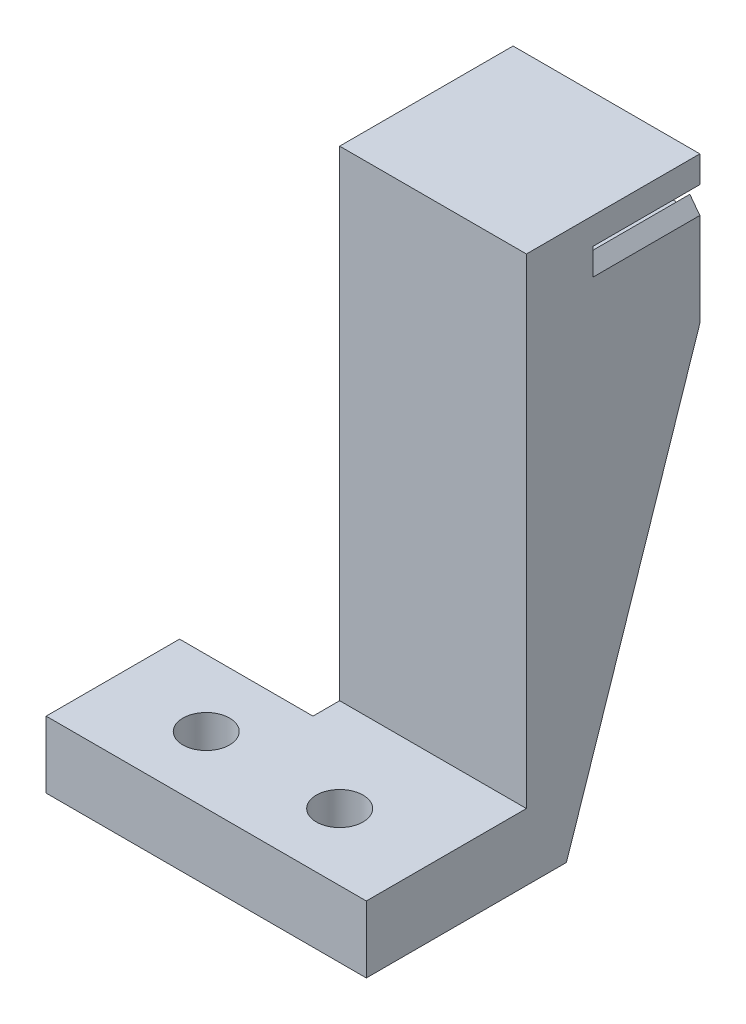
SolidWorks part; units mm, degrees
ref_plane "前视基准面" through (0, 0, 0) normal (0, 0, 1) x (1, 0, 0)
ref_plane "上视基准面" through (0, 0, 0) normal (0, 1, 0) x (1, 0, 0)
ref_plane "右视基准面" through (0, 0, 0) normal (1, 0, 0) x (0, 0, -1)
sketch "草图1" plane through (0, 0, 0) normal (0, 0, 1) x (1, 0, 0)
  line L1 (-22, -13.5) -> (22, -13.5)
  line L2 (-22, -13.5) -> (-22, 13.5)
  line L3 (-22, 13.5) -> (22, 13.5)
  line L4 (22, -13.5) -> (22, 13.5)
  line L5 (-22, -13.5) -> (22, 13.5) construction
  line L6 (-22, 13.5) -> (22, -13.5) construction
  circle A0 centre (-10, 9.5) radius 1.75
  circle A1 centre (-10, -4.5) radius 1.75
  circle A2 centre (10, 9.5) radius 1.75
  circle A3 centre (10, -4.5) radius 1.75
  point P0 (0, 0)
  dimension "D3" = 3.5
  dimension "D4" = 4
  dimension "D5" = 3.5
  dimension "D6" = 14
  dimension "D7" = 20
  dimension "D8" = 4
  dimension "D9" = 3.5
  dimension "D10" = 12
  dimension "D11" = 12
  dimension "D12" = 3.5
  dimension "D13" = 20
  dimension "D14" = 14
  dimension "D1" = 44
  dimension "D2" = 27
extrude "凸台-拉伸1" add sketch "草图1" along normal blind 8
sketch "草图3" plane through (0, 0, 8) normal (0, 0, 1) x (1, 0, 0)
  line L0 (-22, 6) -> (22, 6)
  line L1 (-22, 13.5) -> (-22, -13.5) construction
  line L2 (22, -13.5) -> (22, 13.5) construction
  line L3 (22, 6) -> (22, 13.5)
  line L4 (22, 13.5) -> (-22, 13.5)
  line L5 (-22, 13.5) -> (-22, 6)
  line L6 (-22, 3.5) -> (-17, 3.5)
  line L7 (-17, 3.5) -> (-10, -3.5)
  line L8 (-10, -3.5) -> (-22, -3.5)
  line L9 (-22, -3.5) -> (-22, 3.5)
  line L10 (-13.4645, 3.5) -> (-7.3431, -2.6213)
  line L11 (0, 0) -> (0, -13.5) construction
  line L12 (-22, -13.5) -> (22, -13.5) construction
  line L13 (22, 3.5) -> (17, 3.5)
  line L14 (22, -3.5) -> (22, 3.5)
  line L15 (10, -3.5) -> (22, -3.5)
  line L16 (17, 3.5) -> (10, -3.5)
  line L17 (13.4645, 3.5) -> (7.3431, -2.6213)
  arc A0 (-7.3431, -2.6213) -> (-3.1005, 1.6213) centre (-5.2218, -0.5) ccw
  arc A1 (-13.4645, 3.5) -> (-3.1005, 1.6213) centre (-9.6378, -4.9159) cw
  circle A2 centre (-10, 9.5) radius 3
  arc A3 (7.3431, -2.6213) -> (3.1005, 1.6213) centre (5.2218, -0.5) cw
  arc A4 (13.4645, 3.5) -> (3.1005, 1.6213) centre (9.6378, -4.9159) ccw
  circle A5 centre (10, 9.5) radius 3
  dimension "D7" = 3
  dimension "D8" = 6
  dimension "D1" = 7.5
  dimension "D2" = 7
  dimension "D3" = 2.5
  dimension "D4" = 45
  dimension "D5" = 12
  dimension "D6" = 2.5
  dimension "D9" = 6
extrude "凸台-拉伸2" add sketch "草图3" along normal blind 6.5
sketch "草图4" plane through (0, 0, 8) normal (0, 0, 1) x (1, 0, 0)
  circle A0 centre (-10, -4.5) radius 2.5
  circle A1 centre (10, 9.5) radius 3
  circle A2 centre (10, 9.5) radius 3
  circle A3 centre (-10, 9.5) radius 3
  circle A4 centre (-10, 9.5) radius 3
  circle A5 centre (10, -4.5) radius 2.5
  dimension "D3" = 5
  dimension "D4" = 5
  dimension "D1" = 0
  dimension "D2" = 0
extrude "切除-拉伸1" cut sketch "草图4" against normal blind 2.5
sketch "草图5" plane through (0, 0, 0) normal (0, 0, 1) x (1, 0, 0)
  line L0 (-22, -13.5) -> (22, -13.5)
  line L1 (22, -13.5) -> (22, -31.5)
  line L2 (22, -31.5) -> (-22, -31.5)
  line L3 (-22, -31.5) -> (-22, -13.5)
  dimension "D1" = 18
extrude "凸台-拉伸3" add sketch "草图5" along normal blind 18
sketch "草图6" plane through (0, 0, 18) normal (0, 0, 1) x (1, 0, 0)
  line L0 (-22, -15.5) -> (22, -15.5)
  line L1 (-22, -13.5) -> (-22, -31.5) construction
  line L2 (22, -31.5) -> (22, -13.5) construction
  line L3 (22, -15.5) -> (22, -19.5)
  line L4 (22, -19.5) -> (-22, -19.5)
  line L5 (-22, -19.5) -> (-22, -15.5)
  line L6 (-22, -13.5) -> (22, -13.5) construction
  line L7 (-22, -25.5) -> (22, -25.5)
  line L8 (22, -25.5) -> (22, -29)
  line L9 (22, -29) -> (-22, -29)
  line L10 (-22, -29) -> (-22, -25.5)
  dimension "D1" = 4
  dimension "D2" = 2
  dimension "D3" = 6
  dimension "D4" = 3.5
extrude "切除-拉伸2" cut sketch "草图6" against normal blind 2.5 contours L0 L3 L4 L5
sketch "草图7" plane through (0, 0, 18) normal (0, 0, 1) x (1, 0, 0)
  line L2 (-22, -19.5) -> (22, -19.5) construction
  line L3 (-22, -19.5) -> (22, -19.5) construction
  line L4 (-22, -19.5) -> (-22, -25.5) construction
  circle A0 centre (-12, -22.5) radius 1.75
  circle A1 centre (12, -22.5) radius 1.75
  dimension "D1" = 3.5
  dimension "D2" = 3.5
  dimension "D3" = 24
  dimension "D4" = 10
  dimension "D5" = 3
  dimension "D6" = 3
extrude "切除-拉伸3" cut sketch "草图7" against normal through all
sketch "草图8" plane through (0, 0, 0) normal (0, 0, -1) x (-1, 0, 0)
  line L0 (0, 0) -> (0, -31.5) construction
  line L1 (-15, -25.5) -> (-9, -25.5)
  line L2 (-15, -25.5) -> (-15, -19.5)
  line L3 (-15, -19.5) -> (-9, -19.5)
  line L4 (-9, -25.5) -> (-9, -19.5)
  line L5 (-15, -25.5) -> (-9, -19.5) construction
  line L6 (-15, -19.5) -> (-9, -25.5) construction
  line L7 (22, -31.5) -> (-22, -31.5) construction
  line L8 (15, -19.5) -> (9, -25.5) construction
  line L9 (15, -25.5) -> (9, -19.5) construction
  line L10 (9, -25.5) -> (9, -19.5)
  line L11 (15, -19.5) -> (9, -19.5)
  line L12 (15, -25.5) -> (15, -19.5)
  line L13 (15, -25.5) -> (9, -25.5)
  point P0 (-12, -22.5)
  point P15 (12, -22.5)
  dimension "D1" = 6
  dimension "D2" = 6
extrude "切除-拉伸4" cut sketch "草图8" against normal blind 4
sketch "草图9" plane through (0, 0, 18) normal (0, 0, 1) x (1, 0, 0)
  line L0 (-22, -13.5) -> (22, -13.5)
  line L1 (22, -13.5) -> (22, -31.5)
  line L2 (22, -31.5) -> (-22, -31.5)
  line L3 (-22, -31.5) -> (-22, -13.5)
extrude "切除-拉伸5" cut sketch "草图9" against normal through all
sketch "草图10" plane through (0, -13.5, 0) normal (0, -1, 0) x (1, 0, 0)
  line L0 (-22, 8) -> (22, 8)
  line L1 (22, 8) -> (22, 14.5)
  line L2 (22, 14.5) -> (-22, 14.5)
  line L3 (-22, 14.5) -> (-22, 8)
  line L4 (-22, 8) -> (-21.8348, 7.9647)
  line M4 (22, 8) -> (-22, 8)
extrude "切除-拉伸6" cut sketch "草图10" against normal through all contours L2 L3 L1 M4
sketch "草图11" plane through (0, -13.5, 0) normal (0, -1, 0) x (1, 0, 0)
  line L4 (-22, 8) -> (-22, 0)
  line L5 (-22, 0) -> (22, 0)
  line L6 (22, 0) -> (22, 8)
  line L7 (22, 8) -> (-22, 8)
  line L8 (-22, 8) -> (-22, 0)
  line L9 (-22, 0) -> (22, 0)
  line L10 (22, 0) -> (22, 8)
  line L11 (22, 8) -> (-22, 8)
  dimension "D1" = 0
extrude "凸台-拉伸4" add sketch "草图11" along normal blind 35
sketch "草图12" plane through (0, 0, 8) normal (0, 0, 1) x (1, 0, 0)
  circle A0 centre (-10, -4.5) radius 3
  circle A1 centre (10, -4.5) radius 3
  circle A3 centre (-10, 9.5) radius 3 construction
  dimension "D1" = 6
  dimension "D2" = 6
  dimension "D3" = 14
  dimension "D4" = 20
extrude "切除-拉伸7" cut sketch "草图12" against normal up to surface (2.5 mm away) up to face at (-8.25, -4.5, 5.5)
sketch "草图13" plane through (0, 0, 0) normal (0, 0, -1) x (-1, 0, 0)
  line L0 (-22, -40.5) -> (22, -40.5)
  line L1 (-22, -48.5) -> (-22, 13.5) construction
  line L2 (22, 13.5) -> (22, -48.5) construction
  line L3 (22, -40.5) -> (22, -43.5)
  line L4 (22, -43.5) -> (-22, -43.5)
  line L5 (-22, -43.5) -> (-22, -40.5)
  line L6 (22, -48.5) -> (-22, -48.5) construction
  dimension "D1" = 3
  dimension "D2" = 5
extrude "凸台-拉伸5" add sketch "草图13" along normal blind 10
sketch "草图14" plane through (0, 0, 0) normal (0, 0, -1) x (-1, 0, 0)
  line L0 (-22, -48.5) -> (22, -48.5)
  line L1 (22, -48.5) -> (22, -46.5)
  line L2 (22, -43.5) -> (22, -48.5) construction
  line L3 (-19.25, -45.5) -> (-18.5, -46.5)
  line L4 (-22, -48.5) -> (-22, -43.5) construction
  line L5 (-22, -46.5) -> (-22, -48.5)
  line L6 (-20, -46.5) -> (-19.25, -45.5)
  line L7 (-22, -46.5) -> (-21.25, -45.5)
  line L8 (-17.25, -45.5) -> (-16.5, -46.5)
  line L9 (-21.25, -45.5) -> (-20.5, -46.5)
  line L10 (-18, -46.5) -> (-17.25, -45.5)
  line L11 (-15.25, -45.5) -> (-14.5, -46.5)
  line L12 (-16, -46.5) -> (-15.25, -45.5)
  line L13 (-13.25, -45.5) -> (-12.5, -46.5)
  line L14 (-14, -46.5) -> (-13.25, -45.5)
  line L15 (-11.25, -45.5) -> (-10.5, -46.5)
  line L16 (-12, -46.5) -> (-11.25, -45.5)
  line L17 (-9.25, -45.5) -> (-8.5, -46.5)
  line L18 (-10, -46.5) -> (-9.25, -45.5)
  line L19 (-7.25, -45.5) -> (-6.5, -46.5)
  line L20 (-8, -46.5) -> (-7.25, -45.5)
  line L21 (-5.25, -45.5) -> (-4.5, -46.5)
  line L22 (-6, -46.5) -> (-5.25, -45.5)
  line L23 (-3.25, -45.5) -> (-2.5, -46.5)
  line L24 (-4, -46.5) -> (-3.25, -45.5)
  line L25 (-1.25, -45.5) -> (-0.5, -46.5)
  line L26 (-2, -46.5) -> (-1.25, -45.5)
  line L27 (0.75, -45.5) -> (1.5, -46.5)
  line L28 (0, -46.5) -> (0.75, -45.5)
  line L29 (2.75, -45.5) -> (3.5, -46.5)
  line L30 (2, -46.5) -> (2.75, -45.5)
  line L31 (4.75, -45.5) -> (5.5, -46.5)
  line L32 (4, -46.5) -> (4.75, -45.5)
  line L33 (6.75, -45.5) -> (7.5, -46.5)
  line L34 (6, -46.5) -> (6.75, -45.5)
  line L35 (8.75, -45.5) -> (9.5, -46.5)
  line L36 (8, -46.5) -> (8.75, -45.5)
  line L37 (10.75, -45.5) -> (11.5, -46.5)
  line L38 (10, -46.5) -> (10.75, -45.5)
  line L39 (12.75, -45.5) -> (13.5, -46.5)
  line L40 (12, -46.5) -> (12.75, -45.5)
  line L41 (14.75, -45.5) -> (15.5, -46.5)
  line L42 (14, -46.5) -> (14.75, -45.5)
  line L43 (16.75, -45.5) -> (17.5, -46.5)
  line L44 (16, -46.5) -> (16.75, -45.5)
  line L45 (18.75, -45.5) -> (19.5, -46.5)
  line L46 (18, -46.5) -> (18.75, -45.5)
  line L47 (20.75, -45.5) -> (21.5, -46.5)
  line L48 (20, -46.5) -> (20.75, -45.5)
  line L49 (-20.5, -46.5) -> (-20, -46.5)
  line L50 (-18.5, -46.5) -> (-18, -46.5)
  line L51 (-16.5, -46.5) -> (-16, -46.5)
  line L52 (-14.5, -46.5) -> (-14, -46.5)
  line L53 (-12.5, -46.5) -> (-12, -46.5)
  line L54 (-12, -46.5) -> (-12.0147, -46.4771)
  line L55 (-10.5, -46.5) -> (-10, -46.5)
  line L56 (-8.5, -46.5) -> (-8, -46.5)
  line L57 (-6.5, -46.5) -> (-6, -46.5)
  line L58 (-4.5, -46.5) -> (-4.0515, -46.5)
  line L59 (-4.0515, -46.5) -> (-4, -46.5)
  line L60 (-2.5, -46.5) -> (-2, -46.5)
  line L61 (-0.5, -46.5) -> (0, -46.5)
  line L62 (0, -46.5) -> (-0.004, -46.4905)
  line L63 (1.5, -46.5) -> (2, -46.5)
  line L64 (3.5, -46.5) -> (4, -46.5)
  line L65 (4, -46.5) -> (3.9947, -46.5047)
  line L66 (5.5, -46.5) -> (6, -46.5)
  line L67 (7.5, -46.5) -> (8, -46.5)
  line L68 (9.5, -46.5) -> (9.9467, -46.5)
  line L69 (9.9467, -46.5) -> (10, -46.5)
  line L70 (11.5, -46.5) -> (12, -46.5)
  line L71 (13.5, -46.5) -> (14, -46.5)
  line L72 (14, -46.5) -> (13.9803, -46.4915)
  line L73 (15.5, -46.5) -> (16, -46.5)
  line L74 (16, -46.5) -> (16.0104, -46.4987)
  line L75 (17.5, -46.5) -> (18, -46.5)
  line L76 (19.5, -46.5) -> (20, -46.5)
  line L77 (21.5516, -46.5) -> (22, -46.5)
  line L78 (21.5516, -46.5) -> (21.5, -46.5)
  dimension "D1" = 2
  dimension "D2" = 1.5
  dimension "D3" = 3
  dimension "D4" = 2
  dimension "D5" = 22
extrude "凸台-拉伸6" add sketch "草图14" along normal blind 10
sketch "草图18" plane through (22, 0, 0) normal (1, 0, 0) x (0, 0, -1)
  line L0 (0, -43.5) -> (0, -44.5)
  line L1 (0, -46.5) -> (0, -43.5) construction
  line L2 (0, -44.5) -> (10, -44.5)
  line L3 (10, -44.5) -> (10, -43.5)
  line L4 (10, -43.5) -> (0, -43.5)
  dimension "D1" = 1
extrude "凸台-拉伸8" add sketch "草图18" against normal up to surface (44 mm away) up to face at (-22, -27.15, -3.4)
sketch "草图20" plane through (0, 0, 0) normal (0, 0, -1) x (-1, 0, 0)
  line L0 (-22, -40.5) -> (-22, 13.5) construction
  line L2 (22, -44.5) -> (-22, -44.5) construction
  circle A0 centre (-10, -34.5) radius 1.75
  circle A1 centre (10, -34.5) radius 1.75
  dimension "D1" = 3.5
  dimension "D2" = 3.5
  dimension "D3" = 20
  dimension "D4" = 12
  dimension "D5" = 10
  dimension "D6" = 10
extrude "切除-拉伸11" cut sketch "草图20" against normal blind 10 contours A0
sketch "草图23" plane through (0, 0, 0) normal (0, 0, -1) x (-1, 0, 0)
sketch "草图24" plane through (0, 0, 0) normal (0, 0, -1) x (-1, 0, 0)
  line L0 (-22, -40.5) -> (-22, 13.5) construction
  circle A0 centre (-10, -14.5) radius 1.75
  circle A1 centre (10, -14.5) radius 1.75
  circle A2 centre (10, -34.5) radius 1.75 construction
  circle A3 centre (-10, -34.5) radius 1.75 construction
  dimension "D1" = 3.5
  dimension "D2" = 3.5
  dimension "D3" = 20
  dimension "D4" = 20
  dimension "D5" = 20
  dimension "D6" = 12
extrude "切除-拉伸13" cut sketch "草图24" against normal blind 10 contours A0
sketch "草图26" plane through (0, 0, 8) normal (0, 0, 1) x (1, 0, 0)
  circle A0 centre (-10, -4.5) radius 3 construction
  circle A1 centre (-10, -4.5) radius 3
  circle A3 centre (10, -4.5) radius 3
  circle A4 centre (10, -4.5) radius 3
  dimension "D1" = 0
extrude "凸台-拉伸9" add sketch "草图26" against normal up to surface (8 mm away) up to face at (-11.75, -14.5, 0)
sketch "草图27" plane through (0, 0, 0) normal (0, 0, -1) x (-1, 0, 0)
  line L0 (-22, 13.5) -> (-22, -6.5)
  line L1 (-22, -40.5) -> (-22, 13.5) construction
  line L2 (-22, -6.5) -> (22, -6.5)
  line L3 (22, 13.5) -> (22, -40.5) construction
  line L4 (22, -6.5) -> (22, 13.5)
  line L5 (22, 13.5) -> (-22, 13.5)
  circle A0 centre (-10, -14.5) radius 1.75 construction
  dimension "D1" = 8
extrude "切除-拉伸14" cut sketch "草图27" against normal blind 20
ref_plane "基准面2" through (0, -23.5, 0) normal (0, 1, 0) x (1, 0, 0)
sketch "草图28" plane through (0, 0, 0) normal (0, 0, -1) x (-1, 0, 0)
  line L4 (22, -6.5) -> (-22, -6.5)
  line L5 (-22, -6.5) -> (-22, -40.5)
  line L6 (-22, -40.5) -> (22, -40.5)
  line L7 (22, -40.5) -> (22, -6.5)
  line L8 (22, -6.5) -> (-22, -6.5)
  line L9 (-22, -6.5) -> (-22, -40.5)
  line L10 (-22, -40.5) -> (22, -40.5)
  line L11 (22, -40.5) -> (22, -6.5)
  circle A0 centre (-10, -14.5) radius 1.75 construction
  circle A1 centre (10, -14.5) radius 1.75 construction
  circle A2 centre (10, -34.5) radius 1.75 construction
  circle A3 centre (-10, -14.5) radius 1.75
  circle A4 centre (10, -14.5) radius 1.75
  circle A5 centre (10, -34.5) radius 1.75
  circle A6 centre (-10, -34.5) radius 1.75 construction
  circle A7 centre (-10, -34.5) radius 1.75
  dimension "D1" = 0
extrude "凸台-拉伸11" add sketch "草图28" along normal blind 5 contours L9 L10 L11
ref_plane "基准面5" through (0, -24.5, 0) normal (0, 1, 0) x (1, 0, 0)
mirror "镜向4" about plane through (0, -24.5, 0) normal (0, 1, 0) of bodies 134
sketch "草图30" plane through (0, 0, 0) normal (0, 0, -1) x (-1, 0, 0)
  line L69 (-22, -4.5) -> (22, -4.5)
  line L70 (22, -4.5) -> (22, -2.5)
  line L71 (22, -2.5) -> (21.5, -2.5)
  line L72 (21.5, -2.5) -> (20.75, -3.5)
  line L73 (20.75, -3.5) -> (20, -2.5)
  line L74 (20, -2.5) -> (19.5, -2.5)
  line L75 (19.5, -2.5) -> (18.75, -3.5)
  line L76 (18.75, -3.5) -> (18, -2.5)
  line L77 (18, -2.5) -> (17.5, -2.5)
  line L78 (17.5, -2.5) -> (16.75, -3.5)
  line L79 (16.75, -3.5) -> (16, -2.5)
  line L80 (16, -2.5) -> (15.5, -2.5)
  line L81 (15.5, -2.5) -> (14.75, -3.5)
  line L82 (14.75, -3.5) -> (14, -2.5)
  line L83 (14, -2.5) -> (13.5, -2.5)
  line L84 (13.5, -2.5) -> (12.75, -3.5)
  line L85 (12.75, -3.5) -> (12, -2.5)
  line L86 (12, -2.5) -> (11.5, -2.5)
  line L87 (11.5, -2.5) -> (10.75, -3.5)
  line L88 (10.75, -3.5) -> (10, -2.5)
  line L89 (10, -2.5) -> (9.5, -2.5)
  line L90 (9.5, -2.5) -> (8.75, -3.5)
  line L91 (8.75, -3.5) -> (8, -2.5)
  line L92 (8, -2.5) -> (7.5, -2.5)
  line L93 (7.5, -2.5) -> (6.75, -3.5)
  line L94 (6.75, -3.5) -> (6, -2.5)
  line L95 (6, -2.5) -> (5.5, -2.5)
  line L96 (5.5, -2.5) -> (4.75, -3.5)
  line L97 (4.75, -3.5) -> (4, -2.5)
  line L98 (4, -2.5) -> (3.5, -2.5)
  line L99 (3.5, -2.5) -> (2.75, -3.5)
  line L100 (2.75, -3.5) -> (2, -2.5)
  line L101 (2, -2.5) -> (1.5, -2.5)
  line L102 (1.5, -2.5) -> (0.75, -3.5)
  line L103 (0.75, -3.5) -> (0, -2.5)
  line L104 (0, -2.5) -> (-0.5, -2.5)
  line L105 (-0.5, -2.5) -> (-1.25, -3.5)
  line L106 (-1.25, -3.5) -> (-2, -2.5)
  line L107 (-2, -2.5) -> (-2.5, -2.5)
  line L108 (-2.5, -2.5) -> (-3.25, -3.5)
  line L109 (-3.25, -3.5) -> (-4, -2.5)
  line L110 (-4, -2.5) -> (-4.5, -2.5)
  line L111 (-4.5, -2.5) -> (-5.25, -3.5)
  line L112 (-5.25, -3.5) -> (-6, -2.5)
  line L113 (-6, -2.5) -> (-6.5, -2.5)
  line L114 (-6.5, -2.5) -> (-7.25, -3.5)
  line L115 (-7.25, -3.5) -> (-8, -2.5)
  line L116 (-8, -2.5) -> (-8.5, -2.5)
  line L117 (-8.5, -2.5) -> (-9.25, -3.5)
  line L118 (-9.25, -3.5) -> (-10, -2.5)
  line L119 (-10, -2.5) -> (-10.5, -2.5)
  line L120 (-10.5, -2.5) -> (-11.25, -3.5)
  line L121 (-11.25, -3.5) -> (-12, -2.5)
  line L122 (-12, -2.5) -> (-12.5, -2.5)
  line L123 (-12.5, -2.5) -> (-13.25, -3.5)
  line L124 (-13.25, -3.5) -> (-14, -2.5)
  line L125 (-14, -2.5) -> (-14.5, -2.5)
  line L126 (-14.5, -2.5) -> (-15.25, -3.5)
  line L127 (-15.25, -3.5) -> (-16, -2.5)
  line L128 (-16, -2.5) -> (-16.5, -2.5)
  line L129 (-16.5, -2.5) -> (-17.25, -3.5)
  line L130 (-17.25, -3.5) -> (-18, -2.5)
  line L131 (-18, -2.5) -> (-18.5, -2.5)
  line L132 (-18.5, -2.5) -> (-19.25, -3.5)
  line L133 (-19.25, -3.5) -> (-20, -2.5)
  line L134 (-20, -2.5) -> (-20.5, -2.5)
  line L135 (-20.5, -2.5) -> (-21.25, -3.5)
  line L136 (-21.25, -3.5) -> (-22, -2.5)
  line L137 (-22, -2.5) -> (-22, -4.5)
  line L138 (-22, -4.5) -> (22, -4.5)
  line L139 (22, -4.5) -> (22, -2.5)
  line L140 (22, -2.5) -> (21.5, -2.5)
  line L141 (21.5, -2.5) -> (20.75, -3.5)
  line L142 (20.75, -3.5) -> (20, -2.5)
  line L143 (20, -2.5) -> (19.5, -2.5)
  line L144 (19.5, -2.5) -> (18.75, -3.5)
  line L145 (18.75, -3.5) -> (18, -2.5)
  line L146 (18, -2.5) -> (17.5, -2.5)
  line L147 (17.5, -2.5) -> (16.75, -3.5)
  line L148 (16.75, -3.5) -> (16, -2.5)
  line L149 (16, -2.5) -> (15.5, -2.5)
  line L150 (15.5, -2.5) -> (14.75, -3.5)
  line L151 (14.75, -3.5) -> (14, -2.5)
  line L152 (14, -2.5) -> (13.5, -2.5)
  line L153 (13.5, -2.5) -> (12.75, -3.5)
  line L154 (12.75, -3.5) -> (12, -2.5)
  line L155 (12, -2.5) -> (11.5, -2.5)
  line L156 (11.5, -2.5) -> (10.75, -3.5)
  line L157 (10.75, -3.5) -> (10, -2.5)
  line L158 (10, -2.5) -> (9.5, -2.5)
  line L159 (9.5, -2.5) -> (8.75, -3.5)
  line L160 (8.75, -3.5) -> (8, -2.5)
  line L161 (8, -2.5) -> (7.5, -2.5)
  line L162 (7.5, -2.5) -> (6.75, -3.5)
  line L163 (6.75, -3.5) -> (6, -2.5)
  line L164 (6, -2.5) -> (5.5, -2.5)
  line L165 (5.5, -2.5) -> (4.75, -3.5)
  line L166 (4.75, -3.5) -> (4, -2.5)
  line L167 (4, -2.5) -> (3.5, -2.5)
  line L168 (3.5, -2.5) -> (2.75, -3.5)
  line L169 (2.75, -3.5) -> (2, -2.5)
  line L170 (2, -2.5) -> (1.5, -2.5)
  line L171 (1.5, -2.5) -> (0.75, -3.5)
  line L172 (0.75, -3.5) -> (0, -2.5)
  line L173 (0, -2.5) -> (-0.5, -2.5)
  line L174 (-0.5, -2.5) -> (-1.25, -3.5)
  line L175 (-1.25, -3.5) -> (-2, -2.5)
  line L176 (-2, -2.5) -> (-2.5, -2.5)
  line L177 (-2.5, -2.5) -> (-3.25, -3.5)
  line L178 (-3.25, -3.5) -> (-4, -2.5)
  line L179 (-4, -2.5) -> (-4.5, -2.5)
  line L180 (-4.5, -2.5) -> (-5.25, -3.5)
  line L181 (-5.25, -3.5) -> (-6, -2.5)
  line L182 (-6, -2.5) -> (-6.5, -2.5)
  line L183 (-6.5, -2.5) -> (-7.25, -3.5)
  line L184 (-7.25, -3.5) -> (-8, -2.5)
  line L185 (-8, -2.5) -> (-8.5, -2.5)
  line L186 (-8.5, -2.5) -> (-9.25, -3.5)
  line L187 (-9.25, -3.5) -> (-10, -2.5)
  line L188 (-10, -2.5) -> (-10.5, -2.5)
  line L189 (-10.5, -2.5) -> (-11.25, -3.5)
  line L190 (-11.25, -3.5) -> (-12, -2.5)
  line L191 (-12, -2.5) -> (-12.5, -2.5)
  line L192 (-12.5, -2.5) -> (-13.25, -3.5)
  line L193 (-13.25, -3.5) -> (-14, -2.5)
  line L194 (-14, -2.5) -> (-14.5, -2.5)
  line L195 (-14.5, -2.5) -> (-15.25, -3.5)
  line L196 (-15.25, -3.5) -> (-16, -2.5)
  line L197 (-16, -2.5) -> (-16.5, -2.5)
  line L198 (-16.5, -2.5) -> (-17.25, -3.5)
  line L199 (-17.25, -3.5) -> (-18, -2.5)
  line L200 (-18, -2.5) -> (-18.5, -2.5)
  line L201 (-18.5, -2.5) -> (-19.25, -3.5)
  line L202 (-19.25, -3.5) -> (-20, -2.5)
  line L203 (-20, -2.5) -> (-20.5, -2.5)
  line L204 (-20.5, -2.5) -> (-21.25, -3.5)
  line L205 (-21.25, -3.5) -> (-22, -2.5)
  line L206 (-22, -2.5) -> (-22, -4.5)
  line L207 (22, -44.5) -> (-22, -44.5)
  line L208 (-22, -44.5) -> (-22, -46.5)
  line L209 (-22, -46.5) -> (-21.25, -45.5)
  line L210 (-21.25, -45.5) -> (-20.5, -46.5)
  line L211 (-20.5, -46.5) -> (-20, -46.5)
  line L212 (-20, -46.5) -> (-19.25, -45.5)
  line L213 (-19.25, -45.5) -> (-18.5, -46.5)
  line L214 (-18.5, -46.5) -> (-18, -46.5)
  line L215 (-18, -46.5) -> (-17.25, -45.5)
  line L216 (-17.25, -45.5) -> (-16.5, -46.5)
  line L217 (-16.5, -46.5) -> (-16, -46.5)
  line L218 (-16, -46.5) -> (-15.25, -45.5)
  line L219 (-15.25, -45.5) -> (-14.5, -46.5)
  line L220 (-14.5, -46.5) -> (-14, -46.5)
  line L221 (-14, -46.5) -> (-13.25, -45.5)
  line L222 (-13.25, -45.5) -> (-12.5, -46.5)
  line L223 (-12.5, -46.5) -> (-12, -46.5)
  line L224 (-12, -46.5) -> (-11.25, -45.5)
  line L225 (-11.25, -45.5) -> (-10.5, -46.5)
  line L226 (-10.5, -46.5) -> (-10, -46.5)
  line L227 (-10, -46.5) -> (-9.25, -45.5)
  line L228 (-9.25, -45.5) -> (-8.5, -46.5)
  line L229 (-8.5, -46.5) -> (-8, -46.5)
  line L230 (-8, -46.5) -> (-7.25, -45.5)
  line L231 (-7.25, -45.5) -> (-6.5, -46.5)
  line L232 (-6.5, -46.5) -> (-6, -46.5)
  line L233 (-6, -46.5) -> (-5.25, -45.5)
  line L234 (-5.25, -45.5) -> (-4.5, -46.5)
  line L235 (-4.5, -46.5) -> (-4, -46.5)
  line L236 (-4, -46.5) -> (-3.25, -45.5)
  line L237 (-3.25, -45.5) -> (-2.5, -46.5)
  line L238 (-2.5, -46.5) -> (-2, -46.5)
  line L239 (-2, -46.5) -> (-1.25, -45.5)
  line L240 (-1.25, -45.5) -> (-0.5, -46.5)
  line L241 (-0.5, -46.5) -> (0, -46.5)
  line L242 (0, -46.5) -> (0.75, -45.5)
  line L243 (0.75, -45.5) -> (1.5, -46.5)
  line L244 (1.5, -46.5) -> (2, -46.5)
  line L245 (2, -46.5) -> (2.75, -45.5)
  line L246 (2.75, -45.5) -> (3.5, -46.5)
  line L247 (3.5, -46.5) -> (4, -46.5)
  line L248 (4, -46.5) -> (4.75, -45.5)
  line L249 (4.75, -45.5) -> (5.5, -46.5)
  line L250 (5.5, -46.5) -> (6, -46.5)
  line L251 (6, -46.5) -> (6.75, -45.5)
  line L252 (6.75, -45.5) -> (7.5, -46.5)
  line L253 (7.5, -46.5) -> (8, -46.5)
  line L254 (8, -46.5) -> (8.75, -45.5)
  line L255 (8.75, -45.5) -> (9.5, -46.5)
  line L256 (9.5, -46.5) -> (10, -46.5)
  line L257 (10, -46.5) -> (10.75, -45.5)
  line L258 (10.75, -45.5) -> (11.5, -46.5)
  line L259 (11.5, -46.5) -> (12, -46.5)
  line L260 (12, -46.5) -> (12.75, -45.5)
  line L261 (12.75, -45.5) -> (13.5, -46.5)
  line L262 (13.5, -46.5) -> (14, -46.5)
  line L263 (14, -46.5) -> (14.75, -45.5)
  line L264 (14.75, -45.5) -> (15.5, -46.5)
  line L265 (15.5, -46.5) -> (16, -46.5)
  line L266 (16, -46.5) -> (16.75, -45.5)
  line L267 (16.75, -45.5) -> (17.5, -46.5)
  line L268 (17.5, -46.5) -> (18, -46.5)
  line L269 (18, -46.5) -> (18.75, -45.5)
  line L270 (18.75, -45.5) -> (19.5, -46.5)
  line L271 (19.5, -46.5) -> (20, -46.5)
  line L272 (20, -46.5) -> (20.75, -45.5)
  line L273 (20.75, -45.5) -> (21.5, -46.5)
  line L274 (21.5, -46.5) -> (22, -46.5)
  line L275 (22, -46.5) -> (22, -44.5)
  line L276 (22, -44.5) -> (-22, -44.5)
  line L277 (-22, -44.5) -> (-22, -46.5)
  line L278 (-22, -46.5) -> (-21.25, -45.5)
  line L279 (-21.25, -45.5) -> (-20.5, -46.5)
  line L280 (-20.5, -46.5) -> (-20, -46.5)
  line L281 (-20, -46.5) -> (-19.25, -45.5)
  line L282 (-19.25, -45.5) -> (-18.5, -46.5)
  line L283 (-18.5, -46.5) -> (-18, -46.5)
  line L284 (-18, -46.5) -> (-17.25, -45.5)
  line L285 (-17.25, -45.5) -> (-16.5, -46.5)
  line L286 (-16.5, -46.5) -> (-16, -46.5)
  line L287 (-16, -46.5) -> (-15.25, -45.5)
  line L288 (-15.25, -45.5) -> (-14.5, -46.5)
  line L289 (-14.5, -46.5) -> (-14, -46.5)
  line L290 (-14, -46.5) -> (-13.25, -45.5)
  line L291 (-13.25, -45.5) -> (-12.5, -46.5)
  line L292 (-12.5, -46.5) -> (-12, -46.5)
  line L293 (-12, -46.5) -> (-11.25, -45.5)
  line L294 (-11.25, -45.5) -> (-10.5, -46.5)
  line L295 (-10.5, -46.5) -> (-10, -46.5)
  line L296 (-10, -46.5) -> (-9.25, -45.5)
  line L297 (-9.25, -45.5) -> (-8.5, -46.5)
  line L298 (-8.5, -46.5) -> (-8, -46.5)
  line L299 (-8, -46.5) -> (-7.25, -45.5)
  line L300 (-7.25, -45.5) -> (-6.5, -46.5)
  line L301 (-6.5, -46.5) -> (-6, -46.5)
  line L302 (-6, -46.5) -> (-5.25, -45.5)
  line L303 (-5.25, -45.5) -> (-4.5, -46.5)
  line L304 (-4.5, -46.5) -> (-4, -46.5)
  line L305 (-4, -46.5) -> (-3.25, -45.5)
  line L306 (-3.25, -45.5) -> (-2.5, -46.5)
  line L307 (-2.5, -46.5) -> (-2, -46.5)
  line L308 (-2, -46.5) -> (-1.25, -45.5)
  line L309 (-1.25, -45.5) -> (-0.5, -46.5)
  line L310 (-0.5, -46.5) -> (0, -46.5)
  line L311 (0, -46.5) -> (0.75, -45.5)
  line L312 (0.75, -45.5) -> (1.5, -46.5)
  line L313 (1.5, -46.5) -> (2, -46.5)
  line L314 (2, -46.5) -> (2.75, -45.5)
  line L315 (2.75, -45.5) -> (3.5, -46.5)
  line L316 (3.5, -46.5) -> (4, -46.5)
  line L317 (4, -46.5) -> (4.75, -45.5)
  line L318 (4.75, -45.5) -> (5.5, -46.5)
  line L319 (5.5, -46.5) -> (6, -46.5)
  line L320 (6, -46.5) -> (6.75, -45.5)
  line L321 (6.75, -45.5) -> (7.5, -46.5)
  line L322 (7.5, -46.5) -> (8, -46.5)
  line L323 (8, -46.5) -> (8.75, -45.5)
  line L324 (8.75, -45.5) -> (9.5, -46.5)
  line L325 (9.5, -46.5) -> (10, -46.5)
  line L326 (10, -46.5) -> (10.75, -45.5)
  line L327 (10.75, -45.5) -> (11.5, -46.5)
  line L328 (11.5, -46.5) -> (12, -46.5)
  line L329 (12, -46.5) -> (12.75, -45.5)
  line L330 (12.75, -45.5) -> (13.5, -46.5)
  line L331 (13.5, -46.5) -> (14, -46.5)
  line L332 (14, -46.5) -> (14.75, -45.5)
  line L333 (14.75, -45.5) -> (15.5, -46.5)
  line L334 (15.5, -46.5) -> (16, -46.5)
  line L335 (16, -46.5) -> (16.75, -45.5)
  line L336 (16.75, -45.5) -> (17.5, -46.5)
  line L337 (17.5, -46.5) -> (18, -46.5)
  line L338 (18, -46.5) -> (18.75, -45.5)
  line L339 (18.75, -45.5) -> (19.5, -46.5)
  line L340 (19.5, -46.5) -> (20, -46.5)
  line L341 (20, -46.5) -> (20.75, -45.5)
  line L342 (20.75, -45.5) -> (21.5, -46.5)
  line L343 (21.5, -46.5) -> (22, -46.5)
  line L344 (22, -46.5) -> (22, -44.5)
  dimension "D1" = 0
  dimension "D2" = 0
extrude "切除-拉伸15" cut sketch "草图30" against normal blind 5
sketch "草图31" plane through (0, 0, 8) normal (0, 0, 1) x (1, 0, 0)
  line L0 (-22, -10.5) -> (22, -10.5)
  line L1 (-22, -0.5) -> (-22, -48.5) construction
  line L2 (22, -48.5) -> (22, -0.5) construction
  line L3 (22, -10.5) -> (22, -38.5)
  line L4 (22, -38.5) -> (-22, -38.5)
  line L5 (-22, -38.5) -> (-22, -10.5)
  line L6 (-22, -10.5) -> (-21.849, -10.363)
  line L7 (22, -0.5) -> (-22, -0.5) construction
  line L8 (22, -48.5) -> (-22, -48.5) construction
  circle M1 centre (-10, -14.5) radius 1.75
  circle M2 centre (10, -14.5) radius 1.75
  circle M3 centre (-10, -34.5) radius 1.75
  circle M4 centre (10, -34.5) radius 1.75
  line M5 (-22, -0.5) -> (-22, -48.5)
  line M7 (22, -48.5) -> (22, -0.5)
  dimension "D1" = 10
  dimension "D2" = 10
extrude "切除-拉伸16" cut sketch "草图31" against normal blind 8 contours L4 L0 M7 M5 M2 M4 M3 M1
sketch "草图32" plane through (0, 0, 0) normal (0, 0, 1) x (1, 0, 0)
  circle A0 centre (-10, -14.5) radius 3
  circle A1 centre (10, -14.5) radius 3
  circle A2 centre (10, -34.5) radius 3
  circle A3 centre (-10, -34.5) radius 3
  dimension "D1" = 6
  dimension "D2" = 6
  dimension "D3" = 6
  dimension "D4" = 6
extrude "切除-拉伸17" cut sketch "草图32" against normal blind 3
sketch "草图33" plane through (0, 0, 8) normal (0, 0, 1) x (1, 0, 0)
  line L4 (-22, -10.5) -> (22, -10.5)
  line L5 (22, -10.5) -> (22, -0.5)
  line L6 (22, -0.5) -> (-22, -0.5)
  line L7 (-22, -0.5) -> (-22, -10.5)
  line L8 (-22, -10.5) -> (22, -10.5)
  line L9 (22, -10.5) -> (22, -0.5)
  line L10 (22, -0.5) -> (-22, -0.5)
  line L11 (-22, -0.5) -> (-22, -10.5)
  line L12 (22, -38.5) -> (-22, -38.5)
  line L13 (-22, -38.5) -> (-22, -48.5)
  line L14 (-22, -48.5) -> (22, -48.5)
  line L15 (22, -48.5) -> (22, -38.5)
  line L16 (22, -38.5) -> (-22, -38.5)
  line L17 (-22, -38.5) -> (-22, -48.5)
  line L18 (-22, -48.5) -> (22, -48.5)
  line L19 (22, -48.5) -> (22, -38.5)
  dimension "D1" = 0
  dimension "D2" = 0
extrude "凸台-拉伸12" add sketch "草图33" along normal blind 10
sketch "草图34" plane through (0, -0.5, 0) normal (0, 1, 0) x (1, 0, 0)
  line L0 (0, 0) -> (0, -18) construction
  line L1 (22, -18) -> (-22, -18) construction
  circle A0 centre (-12, -14) radius 1.75
  circle A1 centre (12, -14) radius 1.75
  dimension "D1" = 3.5
  dimension "D2" = 3.5
  dimension "D3" = 24
  dimension "D4" = 12
  dimension "D5" = 4
  dimension "D6" = 4
extrude "切除-拉伸18" cut sketch "草图34" against normal through all
mirror "镜向5"
sketch "草图35" plane through (0, 0, -10) normal (0, 0, -1) x (-1, 0, 0)
  line L0 (-22, -0.5) -> (22, -0.5)
  line L1 (-22, -2.5) -> (-22, 1.5) construction
  line L2 (22, 1.5) -> (22, -2.5) construction
  line L3 (22, -0.5) -> (22, -4.5)
  line L4 (22, -4.5) -> (-22, -4.5)
  line L5 (-22, -4.5) -> (-22, -0.5)
extrude "凸台-拉伸13" add sketch "草图35" against normal up to surface (15 mm away) up to face at (-0.0797, -2.8768, 5)
sketch "草图36" plane through (0, 0, -10) normal (0, 0, -1) x (-1, 0, 0)
  line L0 (-22, 5.5) -> (22, 5.5)
  line L1 (-22, 7.5) -> (-22, 3.5) construction
  line L2 (22, 3.5) -> (22, 7.5) construction
  line L3 (22, 5.5) -> (22, 47.5)
  line L4 (22, 47.5) -> (-22, 47.5)
  line L5 (-22, 47.5) -> (-22, 5.5)
extrude "切除-拉伸19" cut sketch "草图36" against normal through all
sketch "草图37" plane through (0, 0, -10) normal (0, 0, -1) x (-1, 0, 0)
  line L0 (-22, -8.5) -> (22, -8.5)
  line L1 (22, -8.5) -> (22, -2.5)
  line L2 (22, 1.5) -> (22, -8.5) construction
  line L3 (22, -2.5) -> (-22, -2.5)
  line L4 (-22, -8.5) -> (-22, 1.5) construction
  line L5 (-22, -2.5) -> (-22, -8.5)
  line L6 (-22, -8.5) -> (-22.3317, -8.183)
  line L7 (-22, 5.5) -> (22, 5.5) construction
  dimension "D1" = 8
extrude "切除-拉伸20" cut sketch "草图37" against normal up to surface (5 mm away) contours L3 L5 L0 L1 up to face at (8.25, -34.5, -5)
sketch "草图38" plane through (0, 0, -5) normal (0, 0, -1) x (-1, 0, 0)
  line L4 (22, -40.5) -> (22, -2.5)
  line L5 (22, -2.5) -> (-22, -2.5)
  line L6 (-22, -2.5) -> (-22, -40.5)
  line L7 (-22, -40.5) -> (22, -40.5)
  line L8 (22, -40.5) -> (22, -2.5)
  line L9 (22, -2.5) -> (-22, -2.5)
  line L10 (-22, -2.5) -> (-22, -40.5)
  line L11 (-22, -40.5) -> (22, -40.5)
  dimension "D1" = 0
extrude "凸台-拉伸14" add sketch "草图38" against normal up to surface (5 mm away) up to face at (-7, -34.5, 0)
sketch "草图39" plane through (0, 0, -5) normal (0, 0, -1) x (-1, 0, 0)
  line L0 (-22, 5.5) -> (22, 5.5) construction
  line L1 (-22, -2.5) -> (-22, -40.5) construction
  line L2 (0, 0) -> (0, -48.5) construction
  line L3 (-22, -48.5) -> (22, -48.5) construction
  circle A0 centre (-10, -8.5) radius 1.75
  circle A1 centre (10, -8.5) radius 1.75
  dimension "D1" = 14
  dimension "D2" = 12
  dimension "D3" = 3.5
sketch "草图40" plane through (0, 0, 18) normal (0, 0, 1) x (1, 0, 0)
  line L0 (22, -10.5) -> (-22, -10.5)
  line L1 (-22, -10.5) -> (-22, -2.5)
  line L2 (-22, 5.5) -> (-22, -10.5) construction
  line L3 (-22, -2.5) -> (22, -2.5)
  line L4 (22, -10.5) -> (22, 5.5) construction
  line L5 (22, -2.5) -> (22, -10.5)
extrude "切除-拉伸21" cut sketch "草图40" against normal up to surface (18 mm away) up to face at (0, -24.5, 0)
extrude "切除-拉伸22" cut sketch "草图39" against normal blind 10 contours A0
sketch "草图42" plane through (0, 0, -5) normal (0, 0, -1) x (-1, 0, 0)
  line L0 (-22, -18.5) -> (22, -18.5)
  line L1 (-22, -2.5) -> (-22, -40.5) construction
  line L2 (22, -40.5) -> (22, -2.5) construction
  line L3 (-22, -18.5) -> (-22, -48.5)
  line L4 (-22, -48.5) -> (22, -48.5)
  line L5 (22, -48.5) -> (22, -18.5)
  line L6 (22, -18.5) -> (21.8303, -18.4916)
  circle A0 centre (-10, -8.5) radius 1.75 construction
  dimension "D1" = 10
extrude "切除-拉伸24" cut sketch "草图42" against normal through all and the other way blind 10 contours L5 L4 L3 L0
sketch "草图43" plane through (0, 5.5, 0) normal (0, 1, 0) x (1, 0, 0)
  line L0 (-22, -7.807) -> (22, -7.807)
  line L4 (22, 10) -> (-22, 10)
  line L5 (-22, 10) -> (-22, -18)
  line L6 (-22, -18) -> (22, -18)
  line L7 (22, -18) -> (22, 10)
  line L9 (-22, -7.807) -> (-22, -18)
  line L10 (-22, -18) -> (22, -18)
  line L11 (22, -18) -> (22, -7.807)
  dimension "D1" = 0
extrude "凸台-拉伸15" add sketch "草图43" against normal blind 8 contours L0 L11 L10 L9
sketch "草图44" plane through (0, 5.5, 0) normal (0, 1, 0) x (1, 0, 0)
  line L0 (0, 0) -> (0, -18) construction
  line L1 (22, -18) -> (-22, -18) construction
  circle A0 centre (-15, -11) radius 1.75
  circle A1 centre (15, -11) radius 1.75
  dimension "D1" = 3.5
  dimension "D2" = 15
  dimension "D3" = 7
extrude "切除-拉伸25" cut sketch "草图44" against normal blind 8
mirror "镜向6" about plane through (22, -18.5, -15) normal (0, 1, 0) of bodies 154
sketch "草图45" plane through (0, 0, 0) normal (0, 0, 1) x (1, 0, 0)
  circle A0 centre (-10, -28.5) radius 3
  circle A1 centre (-10, -8.5) radius 3
  circle A2 centre (10, -8.5) radius 3
  circle A3 centre (10, -28.5) radius 3
  dimension "D1" = 6
  dimension "D2" = 6
  dimension "D3" = 6
  dimension "D4" = 6
extrude "切除-拉伸26" cut sketch "草图45" against normal blind 3
sketch "草图46" plane through (0, 0, -5) normal (0, 0, -1) x (-1, 0, 0)
  line L0 (22, -34.5) -> (-22, -34.5)
  line L1 (-22, -34.5) -> (-22, -42.5)
  line L2 (-22, -42.5) -> (22, -42.5)
  line L3 (22, -42.5) -> (22, -34.5)
extrude "切除-拉伸27" cut sketch "草图46" against normal through all and the other way through all
sketch "草图47" plane through (-22, 0, 0) normal (-1, 0, 0) x (0, 0, 1)
  line L0 (0, -10.5) -> (8, -2.5)
  line L1 (0, -2.5) -> (0, -34.5) construction
  line L2 (0, -2.5) -> (18, -2.5) construction
  line L3 (8, -2.5) -> (0, -2.5)
  line L4 (0, -2.5) -> (0, -10.5)
  dimension "D1" = 45
  dimension "D2" = 8
extrude "凸台-拉伸16" add sketch "草图47" against normal up to surface (44 mm away) up to face at (22, -4.8333, -0.3333)
sketch "草图48" plane through (0, 0, 0) normal (0, 0, 1) x (1, 0, 0)
  circle A0 centre (-10, -8.5) radius 3
  circle A1 centre (10, -8.5) radius 3
  dimension "D1" = 6
  dimension "D2" = 6
extrude "切除-拉伸28" cut sketch "草图48" along normal blind 10
sketch "草图49" plane through (-22, 0, 0) normal (-1, 0, 0) x (0, 0, 1)
  line L0 (-10, 3.5) -> (-10, 5.5) construction
  line L1 (-2, -36.8175) -> (25.0758, -36.8175)
  line L2 (-2, -0.5) -> (-2, 9.2492)
  line L3 (-2, 9.2492) -> (25.0758, 9.2492)
  line L4 (25.0758, -36.8175) -> (25.0758, 9.2492)
  line L5 (-10, 1.5) -> (-10, -2.5) construction
  line L6 (-10, -0.5) -> (-2, -0.5)
  line L7 (-10, -0.5) -> (-10, -36.8175)
  line L8 (-10, -36.8175) -> (-2, -36.8175)
  line L9 (18, 5.5) -> (-10, 5.5) construction
  dimension "D1" = 8
  dimension "D2" = 6
extrude "切除-拉伸29" cut sketch "草图49" against normal through all
sketch "草图50" plane through (-22, 0, 0) normal (-1, 0, 0) x (0, 0, 1)
  line L1 (-2, -0.5) -> (3, -0.5)
  line L2 (-2, -0.5) -> (-2, 5.5)
  line L3 (-2, 5.5) -> (3, 5.5)
  line L4 (3, -0.5) -> (3, 5.5)
  dimension "D1" = 6
  dimension "D2" = 5
extrude "凸台-拉伸17" add sketch "草图50" against normal up to surface (44 mm away) up to face at (22, 0.5, -6)
sketch "草图51" plane through (0, 5.5, 0) normal (0, 1, 0) x (1, 0, 0)
  line L0 (22, -3) -> (-22, -3) construction
  line L1 (-22, 10) -> (-2, 10)
  line L2 (-22, 10) -> (-22, -3)
  line L3 (-22, -3) -> (-2, -3)
  line L4 (-2, 10) -> (-2, -3)
  line L5 (22, 10) -> (22, -3) construction
  dimension "D1" = 24
extrude "切除-拉伸30" cut sketch "草图51" against normal blind 10
sketch "草图52" plane through (0, -0.5, 0) normal (0, -1, 0) x (1, 0, 0)
  line L1 (22, -10) -> (-2, -10)
  line L2 (22, -10) -> (22, 15)
  line L3 (22, 15) -> (-2, 15)
  line L4 (-2, -10) -> (-2, 15)
  circle A0 centre (15, 10) radius 1.75
  circle A1 centre (5, 10) radius 1.75
  point P9 (10, 15)
  dimension "D3" = 3.5
  dimension "D4" = 3.5
  dimension "D5" = 10
  dimension "D6" = 5
  dimension "D7" = 5
  dimension "D8" = 5
  dimension "D1" = 25
  dimension "D2" = 24
extrude "凸台-拉伸18" add sketch "草图52" along normal blind 35
sketch "草图53" plane through (0, -0.5, 0) normal (0, 1, 0) x (1, 0, 0)
  circle A0 centre (5, -10) radius 3
  circle A1 centre (15, -10) radius 3
  dimension "D1" = 6
  dimension "D2" = 6
extrude "切除-拉伸31" cut sketch "草图53" against normal blind 18
sketch "草图54" plane through (-2, 0, 0) normal (-1, 0, 0) x (0, 0, 1)
  line L1 (-10, -35.5) -> (0, -35.5)
  line L2 (-10, -35.5) -> (-10, -5.5)
  line L3 (-10, -5.5) -> (0, -5.5)
  line L4 (0, -35.5) -> (0, -5.5)
  dimension "D1" = 10
  dimension "D2" = 30
extrude "切除-拉伸32" cut sketch "草图54" against normal through all
sketch "草图55" plane through (0, -0.5, 0) normal (0, 1, 0) x (1, 0, 0)
  line L1 (-2, -15) -> (22, -15)
  line L2 (-2, -15) -> (-2, -3)
  line L3 (-2, -3) -> (22, -3)
  line L4 (22, -15) -> (22, -3)
extrude "切除-拉伸33" cut sketch "草图55" against normal blind 30
sketch "草图56" plane through (-2, 0, 0) normal (-1, 0, 0) x (0, 0, 1)
  line L0 (15, -35.5) -> (0, -35.5) construction
  line L1 (5, -35.5) -> (-10, -35.5)
  line L2 (5, -35.5) -> (5, 5.5)
  line L3 (5, 5.5) -> (-10, 5.5)
  line L4 (-10, -35.5) -> (-10, 5.5)
  line L5 (15, -35.5) -> (15, -30.5) construction
  dimension "D1" = 10
extrude "切除-拉伸34" cut sketch "草图56" against normal blind 10
sketch "草图57" plane through (8, 0, 0) normal (-1, 0, 0) x (0, 0, 1)
  line L0 (0, -35.5) -> (-10, -5.5)
  line L1 (-10, -5.5) -> (0, -5.5)
  line L2 (0, -5.5) -> (0, -35.5)
extrude "凸台-拉伸19" add sketch "草图57" against normal blind 2
sketch "草图58" plane through (22, 0, 0) normal (1, 0, 0) x (0, 0, -1)
  line L3 (0, -5.5) -> (0, -35.5)
  line L4 (0, -35.5) -> (10, -5.5)
  line L5 (10, -5.5) -> (0, -5.5)
  line L6 (0, -5.5) -> (0, -35.5)
  line L7 (0, -35.5) -> (10, -5.5)
  line L8 (10, -5.5) -> (0, -5.5)
  dimension "D1" = 0
extrude "凸台-拉伸20" add sketch "草图58" against normal blind 2
